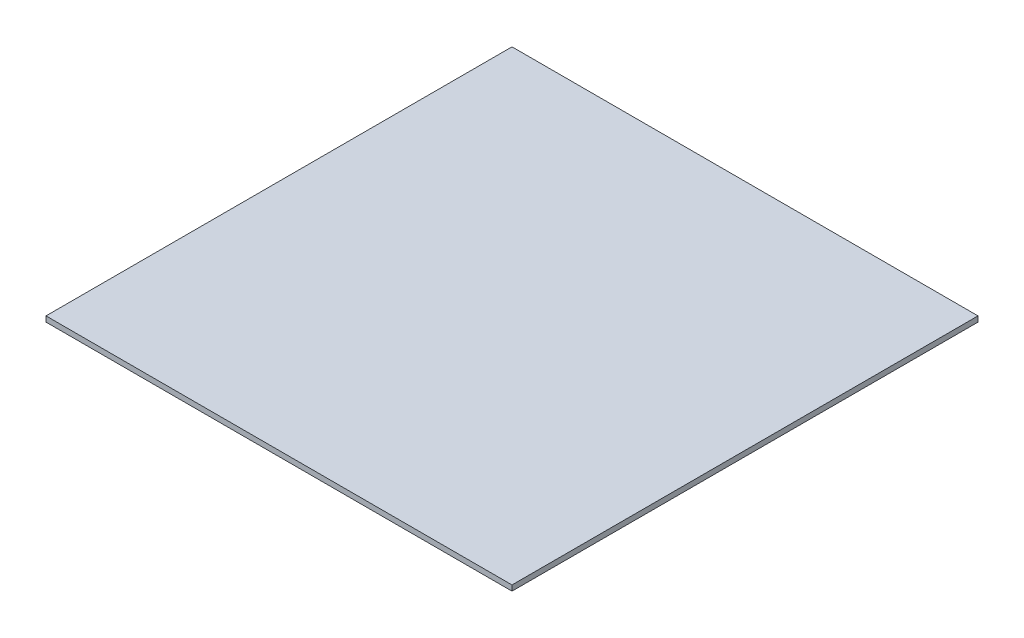
SolidWorks part; units mm, degrees
material "1023 碳钢板 (SS)"
ref_plane "前视基准面" through (0, 0, 0) normal (0, 0, 1) x (1, 0, 0)
ref_plane "上视基准面" through (0, 0, 0) normal (0, 1, 0) x (1, 0, 0)
ref_plane "右视基准面" through (0, 0, 0) normal (1, 0, 0) x (0, 0, -1)
sketch "草图1" plane through (0, 0, 0) normal (0, 1, 0) x (1, 0, 0)
  line L1 (-215, -215) -> (215, -215)
  line L2 (-215, -215) -> (-215, 215)
  line L3 (-215, 215) -> (215, 215)
  line L4 (215, -215) -> (215, 215)
  line L5 (-215, -215) -> (215, 215) construction
  line L6 (-215, 215) -> (215, -215) construction
  point P0 (0, 0)
  dimension "D1" = 430
  dimension "D2" = 430
extrude "凸台-拉伸1" add sketch "草图1" along normal blind 5
